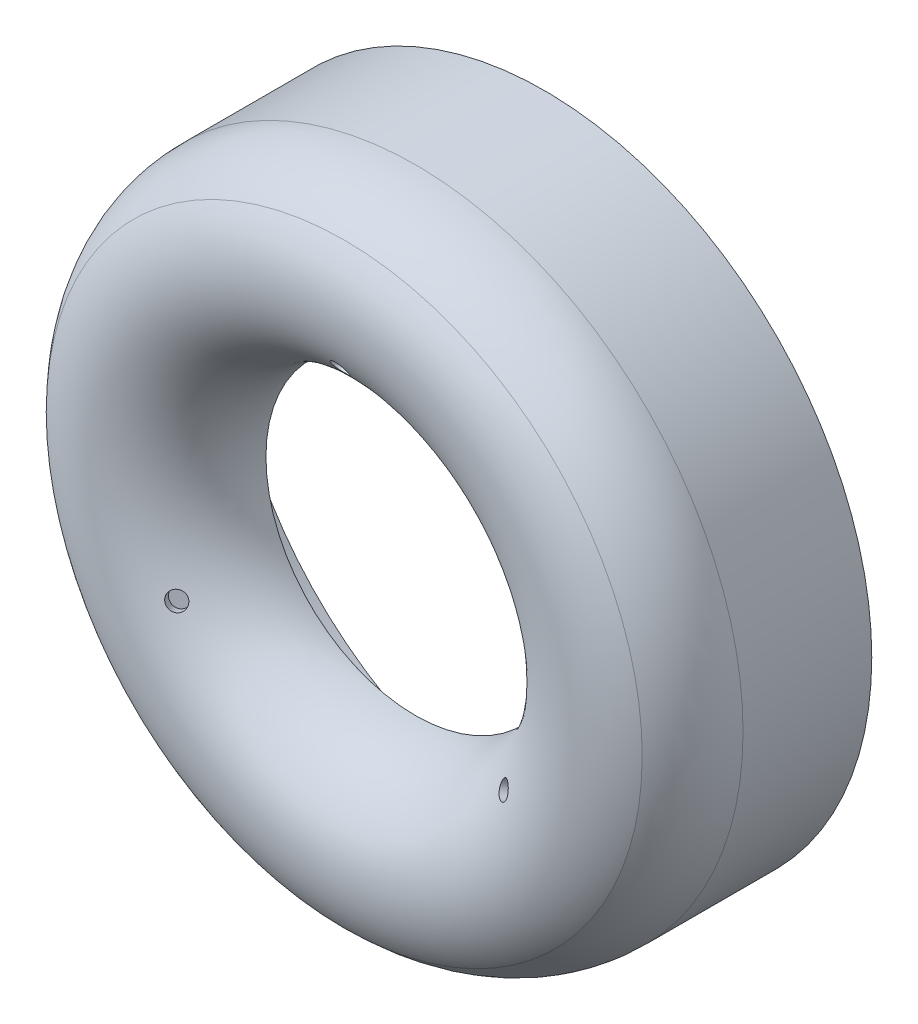
SolidWorks part; units mm, degrees
ref_plane "Plan1" through (0, 0, 0) normal (0, 0, 1) x (1, 0, 0)
ref_plane "Plan2" through (0, 0, 0) normal (0, 1, 0) x (1, 0, 0)
ref_plane "Plan3" through (0, 0, 0) normal (1, 0, 0) x (0, 0, -1)
sketch "Esquisse1" plane through (0, 0, 0) normal (1, 0, 0) x (0, 0, -1)
  line L0 (-53.0037, 0) -> (108.2275, 0) construction
  line L1 (-22.05, 25.5) -> (-22.05, 26.8)
  line L2 (0, 55.85) -> (0, 54.55)
  line L3 (-21.9696, 55.85) -> (0, 55.85)
  line L5 (-22.05, 54.55) -> (0, 54.55)
  arc A0 (-32.69, 49.6822) -> (-22.05, 26.8) centre (-22.05, 40.7148) ccw
  arc A1 (-32.69, 49.6822) -> (-22.05, 54.55) centre (-21.607, 39.5194) cw
  arc A3 (-34.191, 50.8599) -> (-22.05, 25.5) centre (-22.05, 41.0862) ccw
  arc A4 (-34.191, 50.8599) -> (-21.9696, 55.85) centre (-22.1934, 38.9372) cw
  dimension "D1" = 1.3
  dimension "D2" = 1.3
  dimension "D5" = 109.1
  dimension "D3" = 51
revolve "Base-Révolution" add sketch "Esquisse1" angle 360 about L0
sketch "Esquisse2" plane through (0, 0, 0) normal (0, 1, 0) x (1, 0, 0)
  line L0 (0, -53.0037) -> (0, 108.2275) construction
  circle A0 centre (0, -2.5) radius 1.5
  dimension "D1" = 3
  dimension "D2" = 2.5
ref_plane "Plan4" through (0, 57, 0) normal (0, 1, 0) x (-1, 0, 0)
ref_plane "Plan5" through (0, 0, 0) normal (0.342, 0.9397, 0) x (-0.9397, 0.342, 0)
sketch "Esquisse4" plane through (0, 0, 0) normal (0.342, 0.9397, 0) x (-0.9397, 0.342, 0)
  line L0 (0, 25.2803) -> (0, 20) construction
  point P9 (0, 0)
ref_plane "Plan6" through (0, 0, 0) normal (-0.1736, 0.9848, 0) x (-0.9848, -0.1736, 0)
sketch "Esquisse6" plane through (0, -7.4147, 12.8427) normal (0, 0.5, -0.866) x (-1, 0, 0)
  circle A0 centre (0, 45.3564) radius 1.5
  circle A1 centre (0, 45.3564) radius 2.5 construction
  dimension "D1" = 3
extrude "Enlèv. mat.-Extru.5" cut sketch "Esquisse6" along normal blind 3
pattern_circular "Répétition circulaire4" count 3 over 360 about axis through (0, 0, 53.0037) along (0, 0, -1) of "Enlèv. mat.-Extru.5"
